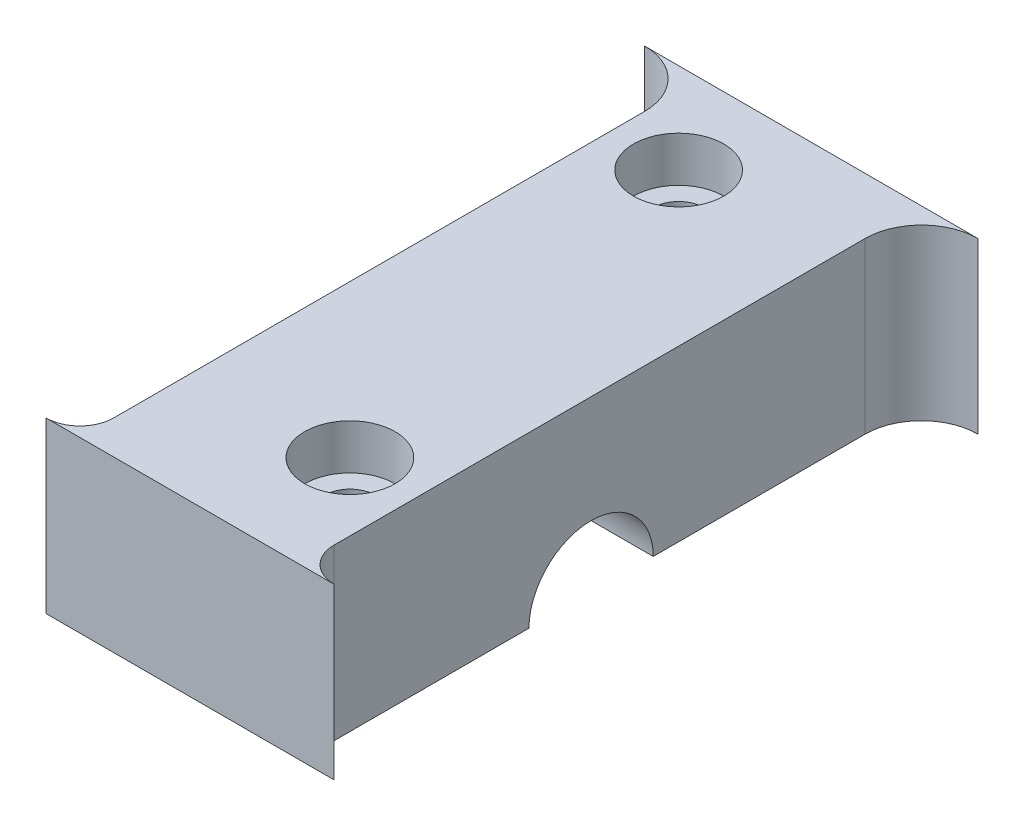
SolidWorks part; units mm, degrees
ref_plane "Plano frontal" through (0, 0, 0) normal (0, 0, 1) x (1, 0, 0)
ref_plane "Plano superior" through (0, 0, 0) normal (0, 1, 0) x (1, 0, 0)
ref_plane "Plano direito" through (0, 0, 0) normal (1, 0, 0) x (0, 0, -1)
sketch "Esboço1" plane through (0, 0, 0) normal (0, 1, 0) x (1, 0, 0)
  line L0 (3, 50) -> (3, 3)
  line L1 (0, 0) -> (25.5, 0)
  line L5 (12.75, 55) -> (12.75, 0) construction
  line L7 (27.5, 55) -> (-2, 55)
  line L8 (22.5, 50) -> (22.5, 3)
  arc A4 (0, 0) -> (3, 3) centre (0, 3) ccw
  arc A7 (-2, 55) -> (3, 50) centre (-2, 50) cw
  arc A8 (27.5, 55) -> (22.5, 50) centre (27.5, 50) ccw
  arc A9 (25.5, 0) -> (22.5, 3) centre (25.5, 3) cw
  dimension "D2" = 5
  dimension "D3" = 3
  dimension "D1" = 47
  dimension "D4" = 3
  dimension "D5" = 3
  dimension "D6" = 5
  dimension "D7" = 5
  dimension "D8" = 19.5
extrude "Corpo" add sketch "Esboço1" along normal blind 15
ref_plane "Plano de Referência" through (12.75, 0, 0) normal (1, 0, 0) x (0, 0, -1)
sketch "Esboço3" plane through (12.75, 0, 0) normal (1, 0, 0) x (0, 0, -1)
  line L1 (55, 15) -> (55, 0) construction
  line L3 (3, 15) -> (50, 15) construction
  circle A0 centre (25.75, 0) radius 5.5
  dimension "D1" = 11
  dimension "D3" = 15
  dimension "D2" = 29.25
extrude "Encaixe Flange - Ø11 Passante" cut sketch "Esboço3" against normal through all and the other way through all
sketch "Esboço4" plane through (12.75, 0, 0) normal (1, 0, 0) x (0, 0, -1)
  circle A0 centre (25.75, 0) radius 11.5
  dimension "D1" = 23
extrude "Encaixe Flange - Ø23x4" cut sketch "Esboço4" against normal blind 2 and the other way blind 2
sketch "Posição dos Furos" plane through (0, 15, 0) normal (0, -1, 0) x (1, 0, 0)
  line L0 (0, 0) -> (25.5, 0) construction
  line L1 (22.5, -3) -> (22.5, -20.25) construction
  line L2 (27.5, -55) -> (-2, -55) construction
  line L3 (3, -50) -> (3, -31.25) construction
  circle A0 centre (16.5, -10.4) radius 1.85
  circle A1 centre (9, -47) radius 1.85
  dimension "D1" = 3.7
  dimension "D2" = 10.4
  dimension "D3" = 6
  dimension "D4" = 8
  dimension "D5" = 6
hole_wizard "Rebaixo M4 - Furos de Fixação" positions "Sketch1" profile "Sketch2" counterbore size "M4" standard "ANSI Metric" end condition through all
sketch "Sketch1" plane through (0, 15, 0) normal (0, 1, 0) x (1, 0, 0)
  point P0 (16.5, 10.4)
  point P3 (9, 47)
sketch "Sketch2" plane through (16.5, 15, -10.4) normal (1, 0, 0) x (0, 0, 1)
  line L0 (0, 0) -> (0, 15)
  line L1 (0, 15) -> (2.25, 15)
  line L3 (2.25, 15) -> (2.25, 4)
  line L4 (2.25, 4) -> (4, 4)
  line L5 (4, 4) -> (4, 0)
  line L7 (4, 0) -> (0, 0)
  line L11 (0, -6.35) -> (0, 107.95) construction
  dimension "Thru Hole Dia." = 4.5
  dimension "Thru Hole Depth" = 15
  dimension "C'Bore Dia." = 8
  dimension "C'Bore Depth" = 4
